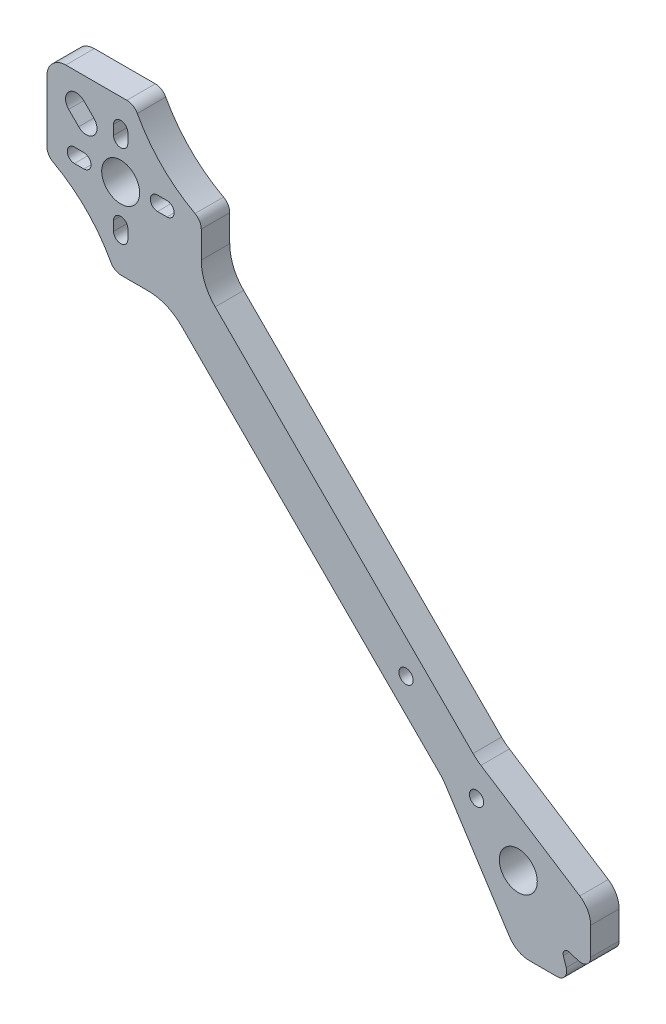
SolidWorks part; units mm, degrees
ref_plane "Alzado" through (0, 0, 0) normal (0, 0, 1) x (1, 0, 0)
ref_plane "Planta" through (0, 0, 0) normal (0, 1, 0) x (1, 0, 0)
ref_plane "Vista lateral" through (0, 0, 0) normal (1, 0, 0) x (0, 0, -1)
sketch "Croquis1" plane through (0, 0, 0) normal (0, 0, 1) x (1, 0, 0)
  line L0 (0, 0) -> (27.8544, 27.8544) construction
  line L1 (0, 0) -> (-42.4264, 42.4264) construction
  line L2 (0, 0) -> (0, 42.4264) construction
  line L3 (15.25, -15.25) -> (-15.25, -15.25) construction
  line L4 (15.25, -15.25) -> (15.25, 15.25) construction
  line L5 (15.25, 15.25) -> (-15.25, 15.25) construction
  line L6 (-15.25, -15.25) -> (-15.25, 15.25) construction
  line L7 (15.25, -15.25) -> (-15.25, 15.25) construction
  line L8 (15.25, 15.25) -> (-15.25, -15.25) construction
  line L9 (0, 42.4264) -> (-20, 42.4264) construction
  line L10 (-42.4264, 42.4264) -> (-38.8909, 45.9619) construction
  line L11 (-38.8909, 45.9619) -> (-31.0962, 38.1673) construction
  line L12 (-20, 42.7635) -> (-20, 80) construction
  line L13 (-42.4264, 42.4264) -> (-45.9619, 38.8909) construction
  line L14 (-45.9619, 38.8909) -> (-38.1673, 31.0962) construction
  line L15 (20, 42.7635) -> (20, 80) construction
  line L16 (38.8909, 45.9619) -> (31.0962, 38.1673) construction
  line L17 (42.4264, 42.4264) -> (38.8909, 45.9619) construction
  line L18 (42.4264, 42.4264) -> (45.9619, 38.8909) construction
  line L19 (-45.9619, -38.8909) -> (-38.1673, -31.0962) construction
  line L20 (0, 0) -> (-15.25, 0) construction
  line L21 (45.9619, 38.8909) -> (38.1673, 31.0962) construction
  line L22 (42.4264, -42.4264) -> (45.9619, -38.8909) construction
  line L23 (42.4264, -42.4264) -> (38.8909, -45.9619) construction
  line L24 (38.8909, -45.9619) -> (31.0962, -38.1673) construction
  line L25 (20, -42.7635) -> (20, -80) construction
  line L26 (-20, -42.7635) -> (-20, -80) construction
  line L27 (-38.8909, -45.9619) -> (-31.0962, -38.1673) construction
  line L28 (-42.4264, -42.4264) -> (-38.8909, -45.9619) construction
  line L29 (-42.4264, -42.4264) -> (-45.9619, -38.8909) construction
  line L30 (45.9619, -38.8909) -> (38.1673, -31.0962) construction
  line L31 (-20, 80) -> (20, 80) construction
  line L32 (0, 80) -> (0, 83) construction
  line L33 (-20, 80) -> (0, 83) construction
  line L34 (0, 83) -> (20, 80) construction
  line L35 (0, -80) -> (0, -83) construction
  line L36 (-20, -80) -> (20, -80) construction
  line L37 (0, -83) -> (20, -80) construction
  line L38 (-20, -80) -> (0, -83) construction
  line L39 (-11, -54) -> (-11, -67.5) construction
  line L41 (-15, -54) -> (-15, -67.5) construction
  line L43 (-13, -54) -> (-13, -67.5) construction
  line L44 (-9, -54) -> (-9, -67.5) construction
  line L45 (-7, -54) -> (-7, -67.5) construction
  line L46 (-5, -54) -> (-5, -67.5) construction
  line L47 (-3, -54) -> (-3, -67.5) construction
  line L48 (-1, -54) -> (-1, -67.5) construction
  line L49 (1, -54) -> (1, -67.5) construction
  line L50 (3, -54) -> (3, -67.5) construction
  line L51 (5, -54) -> (5, -67.5) construction
  line L52 (7, -54) -> (7, -67.5) construction
  line L53 (9, -54) -> (9, -67.5) construction
  line L54 (11, -54) -> (11, -67.5) construction
  line L55 (13, -54) -> (13, -67.5) construction
  line L56 (15, -54) -> (15, -67.5) construction
  line L57 (-11, -35) -> (-11, -48.5) construction
  line L58 (-9, -35) -> (-9, -48.5) construction
  line L59 (-7, -35) -> (-7, -48.5) construction
  line L60 (-5, -35) -> (-5, -48.5) construction
  line L61 (-3, -35) -> (-3, -48.5) construction
  line L62 (-1, -35) -> (-1, -48.5) construction
  line L63 (1, -35) -> (1, -48.5) construction
  line L64 (3, -35) -> (3, -48.5) construction
  line L65 (5, -35) -> (5, -48.5) construction
  line L66 (7, -35) -> (7, -48.5) construction
  line L67 (9, -35) -> (9, -48.5) construction
  line L68 (11, -35) -> (11, -48.5) construction
  line L69 (13, -35) -> (13, -48.5) construction
  line L70 (15, -35) -> (15, -48.5) construction
  line L71 (-15, -35) -> (-15, -48.5) construction
  line L72 (-13, -35) -> (-13, -48.5) construction
  line L73 (-15, 54) -> (-15, 67.5) construction
  line L74 (-13, 35) -> (-13, 48.5) construction
  line L75 (-15, 35) -> (-15, 48.5) construction
  line L76 (15, 35) -> (15, 48.5) construction
  line L77 (13, 35) -> (13, 48.5) construction
  line L78 (11, 35) -> (11, 48.5) construction
  line L79 (9, 35) -> (9, 48.5) construction
  line L80 (7, 35) -> (7, 48.5) construction
  line L81 (5, 35) -> (5, 48.5) construction
  line L82 (3, 35) -> (3, 48.5) construction
  line L83 (1, 35) -> (1, 48.5) construction
  line L84 (-1, 35) -> (-1, 48.5) construction
  line L85 (-3, 35) -> (-3, 48.5) construction
  line L86 (-5, 35) -> (-5, 48.5) construction
  line L87 (-7, 35) -> (-7, 48.5) construction
  line L88 (-9, 35) -> (-9, 48.5) construction
  line L89 (-11, 35) -> (-11, 48.5) construction
  line L90 (15, 54) -> (15, 67.5) construction
  line L91 (13, 54) -> (13, 67.5) construction
  line L92 (11, 54) -> (11, 67.5) construction
  line L93 (9, 54) -> (9, 67.5) construction
  line L94 (7, 54) -> (7, 67.5) construction
  line L95 (5, 54) -> (5, 67.5) construction
  line L96 (3, 54) -> (3, 67.5) construction
  line L97 (1, 54) -> (1, 67.5) construction
  line L98 (-1, 54) -> (-1, 67.5) construction
  line L99 (-3, 54) -> (-3, 67.5) construction
  line L100 (-5, 54) -> (-5, 67.5) construction
  line L101 (-7, 54) -> (-7, 67.5) construction
  line L102 (-9, 54) -> (-9, 67.5) construction
  line L103 (-13, 54) -> (-13, 67.5) construction
  line L104 (-11, 54) -> (-11, 67.5) construction
  line L105 (0, 0) -> (-8.4853, -8.4853) construction
  line L110 (-5.7118, -4.325) -> (-4.3076, -2.2188) construction
  line L111 (-4.325, -5.7118) -> (-2.2188, -4.3076) construction
  line L112 (-4.325, 5.7118) -> (-2.2188, 4.3076) construction
  line L113 (-5.7118, 4.325) -> (-4.3076, 2.2188) construction
  line L114 (5.7118, 4.325) -> (4.3076, 2.2188) construction
  line L115 (4.325, 5.7118) -> (2.2188, 4.3076) construction
  line L116 (4.325, -5.7118) -> (2.2188, -4.3076) construction
  line L117 (5.7118, -4.325) -> (4.3076, -2.2188) construction
  line L123 (-45.9619, 38.8909) -> (-31.0962, 24.0251) construction
  line L124 (-17.1122, 2.2943) -> (-30.516, 23.1236)
  line L125 (-31.8543, 24.7832) -> (-45.9619, 38.8909)
  line L126 (-45.9619, 38.8909) -> (-89.0955, 82.0244)
  line L127 (-31.0962, 24.0251) -> (-24.0251, 31.0962) construction
  line L128 (-38.8909, 45.9619) -> (-24.0251, 31.0962) construction
  line L129 (-2.2943, 17.1122) -> (-23.1236, 30.516)
  line L130 (-24.7832, 31.8543) -> (-38.8909, 45.9619)
  line L131 (-89.0955, 82.0244) -> (-82.0244, 89.0955)
  line L132 (0, 0) -> (-85.5599, 85.5599) construction
  line L135 (-85.5599, 85.5599) -> (-98.9949, 98.9949) construction
  line L168 (-38.8909, 45.9619) -> (-82.0244, 89.0955)
  line L171 (0, 0) -> (-6.364, 6.364) construction
  line L172 (-5.7629, 4.5039) -> (-5.1526, 2.6149)
  line L173 (-7.0557, 0) -> (-12.9076, 0)
  line L174 (-4.5039, 5.7629) -> (-2.6149, 5.1526)
  line L175 (0, 7.0557) -> (0, 12.9076)
  circle A0 centre (-15.25, 15.25) radius 4 construction
  circle A1 centre (-24.0416, 24.0416) radius 1.5 construction
  circle A2 centre (-38.8909, 38.8909) radius 1.5 construction
  arc A3 (-31.0962, 38.1673) -> (-20, 42.7635) centre (-26.5, 42.7635) ccw construction
  arc A4 (31.0962, 38.1673) -> (20, 42.7635) centre (26.5, 42.7635) cw construction
  circle A5 centre (38.8909, 38.8909) radius 1.5 construction
  circle A6 centre (24.0416, 24.0416) radius 1.5 construction
  circle A7 centre (15.25, 15.25) radius 4 construction
  circle A8 centre (15.25, -15.25) radius 4 construction
  circle A9 centre (24.0416, -24.0416) radius 1.5 construction
  circle A10 centre (38.8909, -38.8909) radius 1.5 construction
  arc A11 (31.0962, -38.1673) -> (20, -42.7635) centre (26.5, -42.7635) ccw construction
  circle A12 centre (-15.25, -15.25) radius 4 construction
  circle A13 centre (-24.0416, -24.0416) radius 1.5 construction
  circle A14 centre (-38.8909, -38.8909) radius 1.5 construction
  arc A15 (-31.0962, -38.1673) -> (-20, -42.7635) centre (-26.5, -42.7635) cw construction
  arc A16 (-38.1673, -31.0962) -> (-38.1673, 31.0962) centre (-69.2635, 0) ccw construction
  arc A17 (38.1673, -31.0962) -> (38.1673, 31.0962) centre (69.2635, 0) cw construction
  circle A18 centre (0, 0) radius 1.5 construction
  circle A19 centre (-16, -75) radius 1.5 construction
  circle A20 centre (-16, -30) radius 1.5 construction
  circle A21 centre (-16, 30) radius 1.5 construction
  circle A22 centre (-16, 75) radius 1.5 construction
  circle A23 centre (16, -75) radius 1.5 construction
  circle A24 centre (16, -30) radius 1.5 construction
  circle A25 centre (16, 30) radius 1.5 construction
  circle A26 centre (16, 75) radius 1.5 construction
  arc A27 (-15, -54) -> (-13, -54) centre (-14, -54) cw construction
  arc A28 (-15, -67.5) -> (-13, -67.5) centre (-14, -67.5) ccw construction
  arc A29 (-11, -54) -> (-9, -54) centre (-10, -54) cw construction
  arc A30 (-11, -67.5) -> (-9, -67.5) centre (-10, -67.5) ccw construction
  arc A31 (-7, -54) -> (-5, -54) centre (-6, -54) cw construction
  arc A32 (-7, -67.5) -> (-5, -67.5) centre (-6, -67.5) ccw construction
  arc A33 (-3, -54) -> (-1, -54) centre (-2, -54) cw construction
  arc A34 (-3, -67.5) -> (-1, -67.5) centre (-2, -67.5) ccw construction
  arc A35 (1, -54) -> (3, -54) centre (2, -54) cw construction
  arc A36 (1, -67.5) -> (3, -67.5) centre (2, -67.5) ccw construction
  arc A37 (5, -54) -> (7, -54) centre (6, -54) cw construction
  arc A38 (5, -67.5) -> (7, -67.5) centre (6, -67.5) ccw construction
  arc A39 (9, -54) -> (11, -54) centre (10, -54) cw construction
  arc A40 (9, -67.5) -> (11, -67.5) centre (10, -67.5) ccw construction
  arc A41 (13, -54) -> (15, -54) centre (14, -54) cw construction
  arc A42 (13, -67.5) -> (15, -67.5) centre (14, -67.5) ccw construction
  arc A43 (-11, -35) -> (-9, -35) centre (-10, -35) cw construction
  arc A44 (-11, -48.5) -> (-9, -48.5) centre (-10, -48.5) ccw construction
  arc A45 (-7, -35) -> (-5, -35) centre (-6, -35) cw construction
  arc A46 (-7, -48.5) -> (-5, -48.5) centre (-6, -48.5) ccw construction
  arc A47 (-3, -35) -> (-1, -35) centre (-2, -35) cw construction
  arc A48 (-3, -48.5) -> (-1, -48.5) centre (-2, -48.5) ccw construction
  arc A49 (1, -35) -> (3, -35) centre (2, -35) cw construction
  arc A50 (1, -48.5) -> (3, -48.5) centre (2, -48.5) ccw construction
  arc A51 (5, -35) -> (7, -35) centre (6, -35) cw construction
  arc A52 (5, -48.5) -> (7, -48.5) centre (6, -48.5) ccw construction
  arc A53 (9, -35) -> (11, -35) centre (10, -35) cw construction
  arc A54 (9, -48.5) -> (11, -48.5) centre (10, -48.5) ccw construction
  arc A55 (13, -35) -> (15, -35) centre (14, -35) cw construction
  arc A56 (13, -48.5) -> (15, -48.5) centre (14, -48.5) ccw construction
  arc A57 (-15, -35) -> (-13, -35) centre (-14, -35) cw construction
  arc A58 (-15, -48.5) -> (-13, -48.5) centre (-14, -48.5) ccw construction
  arc A59 (-15, 48.5) -> (-13, 48.5) centre (-14, 48.5) cw construction
  arc A60 (-15, 35) -> (-13, 35) centre (-14, 35) ccw construction
  arc A61 (13, 48.5) -> (15, 48.5) centre (14, 48.5) cw construction
  arc A62 (13, 35) -> (15, 35) centre (14, 35) ccw construction
  arc A63 (9, 48.5) -> (11, 48.5) centre (10, 48.5) cw construction
  arc A64 (9, 35) -> (11, 35) centre (10, 35) ccw construction
  arc A65 (5, 48.5) -> (7, 48.5) centre (6, 48.5) cw construction
  arc A66 (5, 35) -> (7, 35) centre (6, 35) ccw construction
  arc A67 (1, 48.5) -> (3, 48.5) centre (2, 48.5) cw construction
  arc A68 (1, 35) -> (3, 35) centre (2, 35) ccw construction
  arc A69 (-3, 48.5) -> (-1, 48.5) centre (-2, 48.5) cw construction
  arc A70 (-3, 35) -> (-1, 35) centre (-2, 35) ccw construction
  arc A71 (-7, 48.5) -> (-5, 48.5) centre (-6, 48.5) cw construction
  arc A72 (-7, 35) -> (-5, 35) centre (-6, 35) ccw construction
  arc A73 (-11, 48.5) -> (-9, 48.5) centre (-10, 48.5) cw construction
  arc A74 (-11, 35) -> (-9, 35) centre (-10, 35) ccw construction
  arc A75 (13, 67.5) -> (15, 67.5) centre (14, 67.5) cw construction
  arc A76 (13, 54) -> (15, 54) centre (14, 54) ccw construction
  arc A77 (9, 67.5) -> (11, 67.5) centre (10, 67.5) cw construction
  arc A78 (9, 54) -> (11, 54) centre (10, 54) ccw construction
  arc A79 (5, 67.5) -> (7, 67.5) centre (6, 67.5) cw construction
  arc A80 (5, 54) -> (7, 54) centre (6, 54) ccw construction
  arc A81 (1, 67.5) -> (3, 67.5) centre (2, 67.5) cw construction
  arc A82 (1, 54) -> (3, 54) centre (2, 54) ccw construction
  arc A83 (-3, 67.5) -> (-1, 67.5) centre (-2, 67.5) cw construction
  arc A84 (-3, 54) -> (-1, 54) centre (-2, 54) ccw construction
  arc A85 (-7, 67.5) -> (-5, 67.5) centre (-6, 67.5) cw construction
  arc A86 (-7, 54) -> (-5, 54) centre (-6, 54) ccw construction
  arc A87 (-11, 67.5) -> (-9, 67.5) centre (-10, 67.5) cw construction
  arc A88 (-11, 54) -> (-9, 54) centre (-10, 54) ccw construction
  arc A89 (-15, 67.5) -> (-13, 67.5) centre (-14, 67.5) cw construction
  arc A90 (-15, 54) -> (-13, 54) centre (-14, 54) ccw construction
  arc A91 (-4.325, -5.7118) -> (-5.7118, -4.325) centre (-4.8797, -4.8797) cw construction
  arc A92 (-5.7118, 4.325) -> (-4.325, 5.7118) centre (-4.8797, 4.8797) cw construction
  arc A93 (4.325, 5.7118) -> (5.7118, 4.325) centre (4.8797, 4.8797) cw construction
  arc A94 (5.7118, -4.325) -> (4.325, -5.7118) centre (4.8797, -4.8797) cw construction
  circle A95 centre (0, 0) radius 1.5 construction
  arc A96 (2.2188, -4.3076) -> (-2.2188, -4.3076) centre (0, -7.6358) ccw construction
  arc A97 (4.3076, 2.2188) -> (4.3076, -2.2188) centre (7.6358, 0) ccw construction
  arc A98 (-2.2188, 4.3076) -> (2.2188, 4.3076) centre (0, 7.6358) ccw construction
  arc A99 (-4.3076, 2.2188) -> (-4.3076, -2.2188) centre (-7.6358, 0) cw construction
  circle A102 centre (-38.8909, 38.8909) radius 1.5
  circle A103 centre (-24.0416, 24.0416) radius 1.5
  circle A104 centre (-15.25, 15.25) radius 4
  arc A112 (0, 12.9076) -> (-2.2943, 17.1122) centre (-5, 12.9076) ccw
  arc A113 (-12.9076, 0) -> (-17.1122, 2.2943) centre (-12.9076, 5) cw
  arc A114 (-23.1236, 30.516) -> (-24.7832, 31.8543) centre (-17.7121, 38.9253) cw
  arc A115 (-31.8543, 24.7832) -> (-30.516, 23.1236) centre (-38.9253, 17.7121) cw
  arc A143 (-4.5039, 5.7629) -> (-5.7629, 4.5039) centre (-4.8114, 4.8114) ccw
  arc A144 (-2.6149, 5.1526) -> (0, 7.0557) centre (-2, 7.0557) ccw
  arc A145 (-5.1526, 2.6149) -> (-7.0557, 0) centre (-7.0557, 2) cw
  circle A146 centre (-98.9949, 98.9949) radius 76.5 construction
  point P35 (-34.9935, 42.0646)
  point P37 (44.1942, 40.6586)
  point P45 (44.1942, -40.6586)
  point P61 (-34.9935, -42.0646)
  point P305 (0, 0)
  point P308 (-2.8284, 0)
  point P327 (0, 4.3076)
  point P330 (-4.3076, 0)
  point P338 (0, 15.6358)
  point P341 (-15.6358, 0)
  dimension "D2" = 8
  dimension "D4" = 5
  dimension "D8" = 6.5
  dimension "D10" = 3
  dimension "D11" = 3
  dimension "D13" = 4
  dimension "D15" = 3
  dimension "D16" = 3
  dimension "D18" = 45
  dimension "D26" = 1
  dimension "D28" = 4
  dimension "D29" = 19
  dimension "D31" = 153
  dimension "D32" = 9
  dimension "D33" = 5
  dimension "D34" = 10
  dimension "D39" = 1
  dimension "D40" = 2
  dimension "D30" = 5
  dimension "D1" = 30.5
  dimension "D3" = 60
  dimension "D5" = 21
  dimension "D6" = 20
  dimension "D7" = 5
  dimension "D9" = 5
  dimension "D12" = 80
  dimension "D14" = 5
  dimension "D17" = 4
  dimension "D19" = 2
  dimension "D20" = 13.5
  dimension "D21" = 7.5
  dimension "D22" = 5
  dimension "D25" = 12
  dimension "D35" = 140
  dimension "D23" = 8
  dimension "D24" = 2
  dimension "D27" = 4
extrude "Saliente-Extruir1" add sketch "Croquis1" along normal blind 6
sketch "Croquis4" plane through (0, 0, 6) normal (0, 0, 1) x (1, 0, 0)
  line L0 (-89.0955, 82.0244) -> (-100.4092, 82.0244)
  line L1 (-100.4092, 82.0244) -> (-114.5513, 96.1665)
  line L2 (-98.9949, 98.9949) -> (-114.5513, 114.5513) construction
  line L3 (-114.5513, 96.1665) -> (-114.5513, 114.5513)
  line L4 (-82.0244, 89.0955) -> (-82.0244, 100.4092)
  line L5 (-82.0244, 100.4092) -> (-96.1665, 114.5513)
  line L6 (-96.1665, 114.5513) -> (-114.5513, 114.5513)
  line L7 (-89.0955, 82.0244) -> (-82.0244, 89.0955)
  circle A0 centre (-98.9949, 98.9949) radius 4
  dimension "D1" = 22
  dimension "D2" = 13
extrude "Saliente-Extruir3" add sketch "Croquis4" against normal up to vertex (6 mm away)
sketch "Croquis5" plane through (0, 0, 6) normal (0, 0, 1) x (1, 0, 0)
  line L0 (-98.9949, 98.9949) -> (-114.5513, 114.5513) construction
  line L2 (-109.9551, 106.7731) -> (-107.8338, 104.6518)
  line L4 (-104.6518, 107.8338) -> (-106.7731, 109.9551)
  line L6 (-101.8234, 101.8234) -> (-104.6518, 104.6518) construction
  line L7 (-98.9949, 98.9949) -> (-82.0244, 98.9949) construction
  line L8 (-100.4949, 91.2449) -> (-100.4949, 89.2449)
  line L9 (-91.2449, 97.4949) -> (-89.2449, 97.4949)
  line L11 (-91.2449, 100.4949) -> (-89.2449, 100.4949)
  line L13 (-97.4949, 91.2449) -> (-97.4949, 89.2449)
  line L14 (-106.7449, 100.4949) -> (-108.7449, 100.4949)
  line L15 (-106.7449, 97.4949) -> (-108.7449, 97.4949)
  line L16 (-97.4949, 106.7449) -> (-97.4949, 108.7449)
  line L17 (-100.4949, 106.7449) -> (-100.4949, 108.7449)
  arc A0 (-109.9551, 106.7731) -> (-106.7731, 109.9551) centre (-108.3641, 108.3641) cw
  arc A1 (-107.8338, 104.6518) -> (-104.6518, 107.8338) centre (-106.2428, 106.2428) ccw
  circle A2 centre (-98.9949, 98.9949) radius 4 construction
  arc A3 (-89.2449, 100.4949) -> (-89.2449, 97.4949) centre (-89.2449, 98.9949) cw
  arc A4 (-91.2449, 97.4949) -> (-91.2449, 100.4949) centre (-91.2449, 98.9949) cw
  arc A5 (-97.4949, 89.2449) -> (-100.4949, 89.2449) centre (-98.9949, 89.2449) cw
  arc A6 (-100.4949, 91.2449) -> (-97.4949, 91.2449) centre (-98.9949, 91.2449) cw
  arc A7 (-108.7449, 97.4949) -> (-108.7449, 100.4949) centre (-108.7449, 98.9949) cw
  arc A8 (-106.7449, 100.4949) -> (-106.7449, 97.4949) centre (-106.7449, 98.9949) cw
  arc A9 (-100.4949, 108.7449) -> (-97.4949, 108.7449) centre (-98.9949, 108.7449) cw
  arc A10 (-97.4949, 106.7449) -> (-100.4949, 106.7449) centre (-98.9949, 106.7449) cw
  point P23 (-92.7449, 98.9949)
  point P43 (-98.9949, 98.9949)
  dimension "D1" = 3
  dimension "D2" = 4
  dimension "D3" = 4.5
  dimension "D4" = 2.25
  dimension "D5" = 3
  dimension "D6" = 1.5
  dimension "D7" = 2
  dimension "D8" = 6.25
extrude "Cortar-Extruir1" cut sketch "Croquis5" against normal up to vertex (6 mm away)
fillet "Redondeo3" radius 4 1 edges at (-114.5513, 114.5513, 3)
sketch "Croquis7" plane through (0, 0, 6) normal (0, 0, 1) x (1, 0, 0)
  line L0 (-114.5513, 96.1665) -> (-100.4092, 82.0244)
  line L3 (-98.9949, 98.9949) -> (-82.0244, 82.0244) construction
  line L4 (-96.1665, 114.5513) -> (-82.0244, 100.4092)
  arc A0 (-114.5513, 96.1665) -> (-100.4092, 82.0244) centre (-127.4802, 69.0955) cw
  arc A1 (-96.1665, 114.5513) -> (-82.0244, 100.4092) centre (-69.0955, 127.4802) ccw
  dimension "D1" = 30
extrude "Cortar-Extruir2" cut sketch "Croquis7" against normal up to vertex (6 mm away)
fillet "Redondeo4" radius 2.5 4 edges at (-96.1665, 114.5513, 3) (-82.0244, 100.4092, 3) (-100.4092, 82.0244, 3) (-114.5513, 96.1665, 3)
fillet "Redondeo6" radius 10 2 edges at (-82.0244, 89.0955, 3) (-89.0955, 82.0244, 3)
